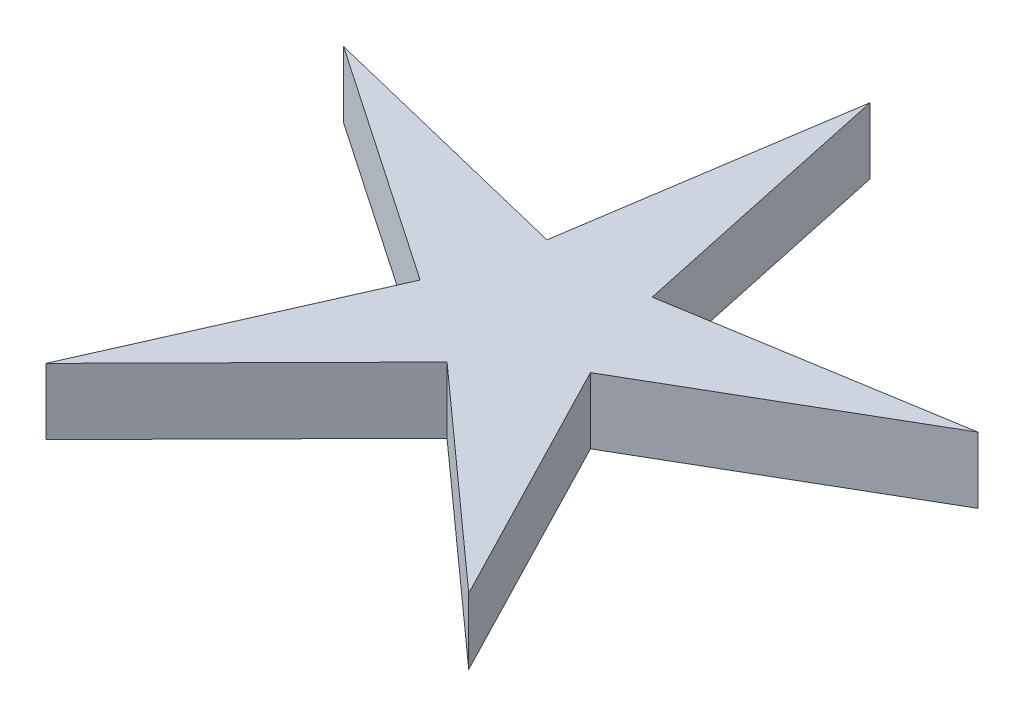
SolidWorks part; units mm, degrees
ref_plane "前视基准面" through (0, 0, 0) normal (0, 0, 1) x (1, 0, 0)
ref_plane "上视基准面" through (0, 0, 0) normal (0, 1, 0) x (1, 0, 0)
ref_plane "右视基准面" through (0, 0, 0) normal (1, 0, 0) x (0, 0, -1)
other "Configuration Table"
sketch "草图1" plane through (0, 0, 0) normal (0, 1, 0) x (1, 0, 0)
  line L0 (34.1194, 11.0178) -> (83.9198, 28.8669) construction
  line L7 (34.1194, 11.0178) -> (4.3215, -32.6943) construction
  line L8 (34.1194, 11.0178) -> (66.484, -30.8295) construction
  line L9 (34.1194, 11.0178) -> (-14.6991, 31.3998) construction
  line L10 (32.533, 63.8965) -> (26.061, 21.4372)
  line L11 (26.061, 21.4372) -> (-14.6991, 31.3998)
  line L12 (-14.6991, 31.3998) -> (21.7198, 6.5736)
  line L13 (21.7198, 6.5736) -> (4.3215, -32.6943)
  line L14 (4.3215, -32.6943) -> (34.5144, -2.1483)
  line L15 (34.5144, -2.1483) -> (66.484, -30.8295)
  line L16 (66.484, -30.8295) -> (46.7631, 7.3249)
  line L17 (46.7631, 7.3249) -> (83.9198, 28.8669)
  line L18 (83.9198, 28.8669) -> (41.5387, 21.9015)
  line L19 (41.5387, 21.9015) -> (32.533, 63.8965)
  line L20 (34.1194, 11.0178) -> (32.533, 63.8965) construction
  circle A1 centre (34.1194, 11.0178) radius 13.172 construction
  circle A2 centre (34.1194, 11.0178) radius 52.9024 construction
  point P0 (34.5144, -2.1483)
  point P1 (26.061, 21.4372)
  point P7 (16.2713, 7.8737)
  point P8 (-31.3933, 37.009)
  point P9 (41.5387, 21.9015)
  point P10 (46.7631, 7.3249)
  point P11 (34.5144, -2.1483)
  point P12 (21.7198, 6.5736)
  point P21 (21.7198, 6.5736)
  point P22 (0, 0)
extrude "凸台-拉伸1" add sketch "草图1" along normal blind 10
